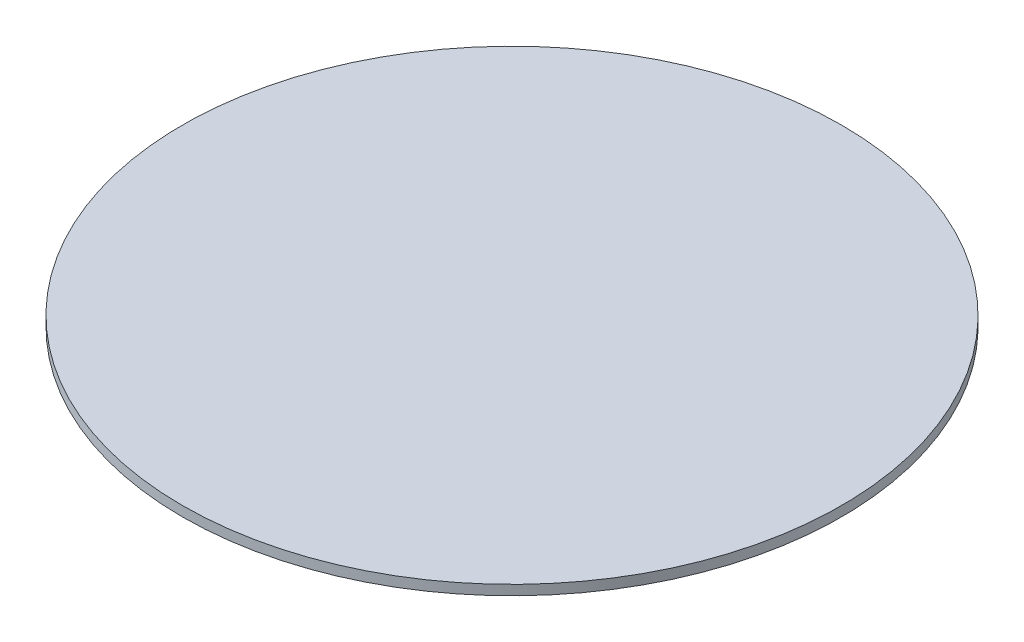
SolidWorks part; units mm, degrees
material "Glass"
ref_plane "Front Plane" through (0, 0, 0) normal (0, 0, 1) x (1, 0, 0)
ref_plane "Top Plane" through (0, 0, 0) normal (0, 1, 0) x (1, 0, 0)
ref_plane "Right Plane" through (0, 0, 0) normal (1, 0, 0) x (0, 0, -1)
sketch "Sketch2" plane through (0, 0, 0) normal (0, 1, 0) x (1, 0, 0)
  circle A0 centre (0, 0) radius 50
  dimension "D1" = 100
extrude "Boss-Extrude1" add sketch "Sketch2" along normal blind 1.5
